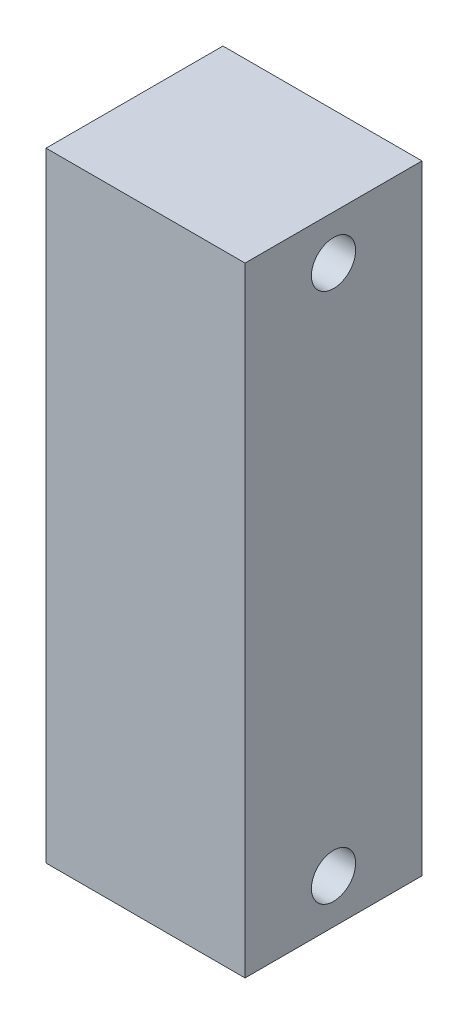
SolidWorks part; units mm, degrees
ref_plane "Front Plane" through (0, 0, 0) normal (0, 0, 1) x (1, 0, 0)
ref_plane "Top Plane" through (0, 0, 0) normal (0, 1, 0) x (1, 0, 0)
ref_plane "Right Plane" through (0, 0, 0) normal (1, 0, 0) x (0, 0, -1)
sketch "Sketch1" plane through (0, 0, 0) normal (0, 1, 0) x (1, 0, 0)
  line L1 (-22.5, -20) -> (22.5, -20)
  line L2 (-22.5, -20) -> (-22.5, 20)
  line L3 (-22.5, 20) -> (22.5, 20)
  line L4 (22.5, -20) -> (22.5, 20)
  line L5 (-22.5, -20) -> (22.5, 20) construction
  line L6 (-22.5, 20) -> (22.5, -20) construction
  point P0 (0, 0)
  dimension "D1" = 45
  dimension "D2" = 40
extrude "Boss-Extrude1" add sketch "Sketch1" along normal blind 140
sketch "Sketch2" plane through (22.5, 0, 0) normal (1, 0, 0) x (0, 0, -1)
  line L4 (-20, 0) -> (20, 0)
  line L5 (20, 0) -> (20, 140)
  line L6 (20, 140) -> (-20, 140)
  line L7 (-20, 140) -> (-20, 0)
  line L8 (-20, 0) -> (20, 0)
  line L9 (20, 0) -> (20, 140)
  line L10 (20, 140) -> (-20, 140)
  line L11 (-20, 140) -> (-20, 0)
  circle A0 centre (0, 10) radius 5
  circle A1 centre (0, 130) radius 5
  point P8 (0, 15.4122)
  point P9 (0, 0)
  point P10 (0, 0)
  point P11 (0, 0)
  point P12 (0, 140)
  dimension "D4" = 10
  dimension "D5" = 10
  dimension "D2" = 120
  dimension "D3" = 10
  dimension "D1" = 0
extrude "Cut-Extrude1" cut sketch "Sketch2" against normal up to surface (45 mm away) contours A1 | A0 up to face at (-22.5, 70, 0)
